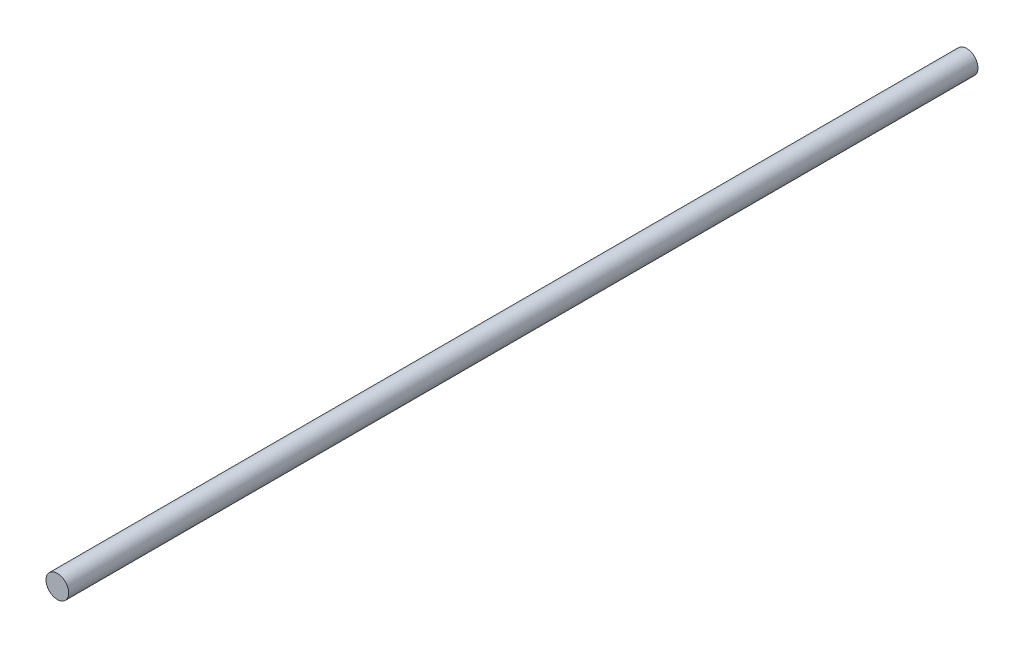
SolidWorks part; units mm, degrees
ref_plane "Front Plane" through (0, 0, 0) normal (0, 0, 1) x (1, 0, 0)
ref_plane "Top Plane" through (0, 0, 0) normal (0, 1, 0) x (1, 0, 0)
ref_plane "Right Plane" through (0, 0, 0) normal (1, 0, 0) x (0, 0, -1)
sketch "Sketch1" plane through (0, 0, 0) normal (0, 0, 1) x (1, 0, 0)
  circle A0 centre (35, -7.5) radius 2
  dimension "D1" = 4
extrude "Boss-Extrude1" add sketch "Sketch1" along normal blind 15 and the other way blind 145
